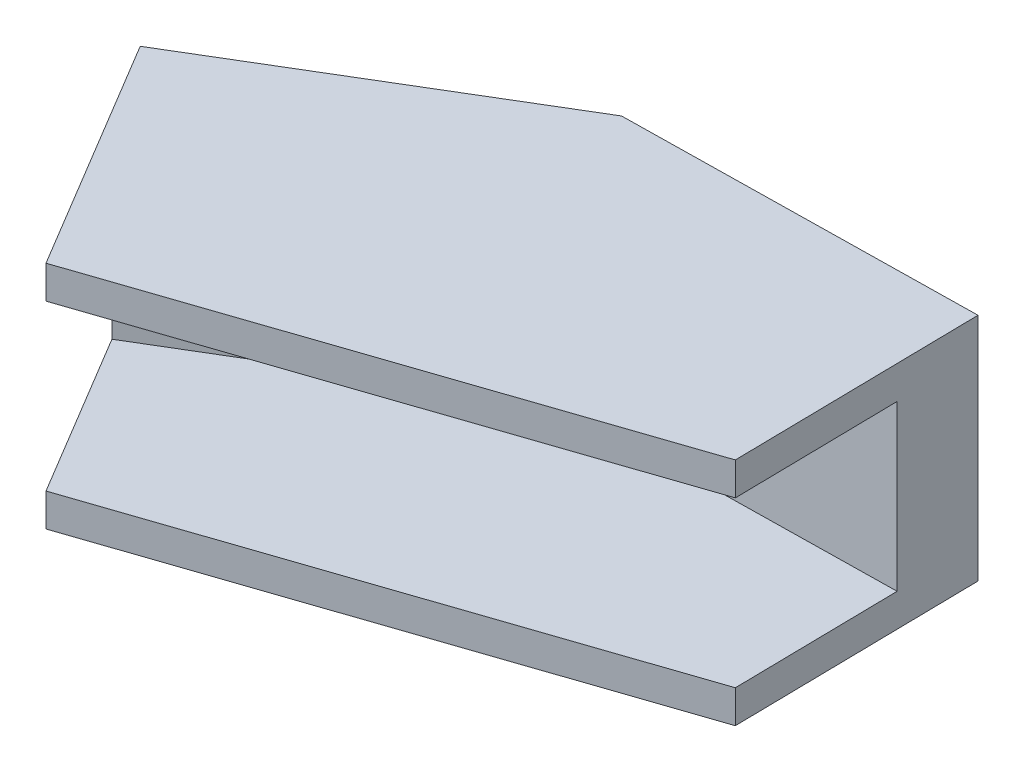
SolidWorks part; units mm, degrees
ref_plane "Front Plane" through (0, 0, 0) normal (0, 0, 1) x (1, 0, 0)
ref_plane "Top Plane" through (0, 0, 0) normal (0, 1, 0) x (1, 0, 0)
ref_plane "Right Plane" through (0, 0, 0) normal (1, 0, 0) x (0, 0, -1)
sketch "Sketch3" plane through (0, 0, 0) normal (0, 1, 0) x (1, 0, 0)
  line L0 (0, 0) -> (19.9974, 0.3225)
  line L1 (0, 0) -> (-17.157, -10.278)
  line L2 (-1.4202, 4.9777) -> (19.9168, 5.3219)
  line L3 (-1.4202, 4.9777) -> (-19.7265, -5.9888)
  line L4 (-19.7265, -5.9888) -> (-17.157, -10.278)
  line L5 (-17.157, -10.278) -> (-16.777, -10.4215)
  line L6 (19.9168, 5.3219) -> (19.9974, 0.3225)
  dimension "D1" = 20
  dimension "D2" = 20
  dimension "D3" = 150
  dimension "D4" = 5
extrude "Boss-Extrude1" add sketch "Sketch3" along normal blind 10 contours L6 L2 L3 L4 L1 L0
sketch "Sketch4" plane through (0, 10, 0) normal (0, 1, 0) x (1, 0, 0)
  line L0 (-19.7265, -5.9888) -> (-17.157, -10.278)
  line L1 (-19.7265, -5.9888) -> (-1.4202, 4.9777)
  line L2 (-1.4202, 4.9777) -> (19.9168, 5.3219)
  line L3 (19.9168, 5.3219) -> (19.9974, 0.3225)
  line L4 (19.9974, 0.3225) -> (20.1587, -9.6775)
  line L5 (-17.157, -10.278) -> (-11.1664, -20.278)
  line L6 (-11.1664, -20.278) -> (20.1587, -9.6775)
  dimension "D1" = 10
  dimension "D2" = 10
extrude "Boss-Extrude2" add sketch "Sketch4" along normal blind 2
ref_plane "Plane1" through (0, 5, 0) normal (0, 1, 0) x (1, 0, 0)
mirror "Mirror1" about plane through (0, 5, 0) normal (0, 1, 0) of "Boss-Extrude2", "Boss-Extrude1"
